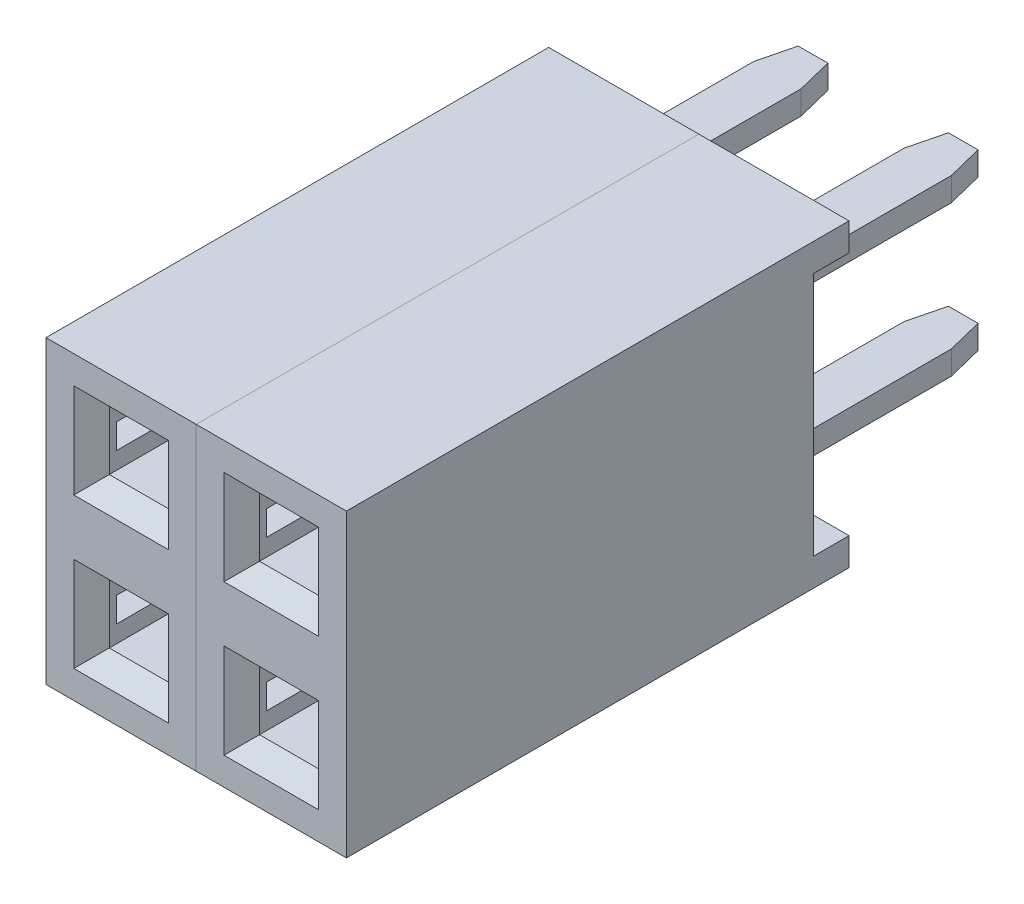
SolidWorks part; units mm, degrees
ref_plane "Спереди" through (0, 0, 0) normal (0, 0, 1) x (1, 0, 0)
ref_plane "Сверху" through (0, 0, 0) normal (0, 1, 0) x (1, 0, 0)
ref_plane "Справа" through (0, 0, 0) normal (1, 0, 0) x (0, 0, -1)
other "HX2.54D-Female"
sketch "Эскиз1" plane through (0, 0, 0) normal (0, 0, 1) x (1, 0, 0)
  line L0 (0, 1.27) -> (0, 0) construction
  line L1 (1.27, 2.54) -> (-1.27, 2.54)
  line L2 (1.27, 2.54) -> (1.27, 0)
  line L3 (1.27, 0) -> (-1.27, 0)
  line L4 (-1.27, 2.54) -> (-1.27, 0)
  line L5 (1.27, 2.54) -> (-1.27, 0) construction
  line L6 (1.27, 0) -> (-1.27, 2.54) construction
  dimension "D1" = 2.54
extrude "Бобышка-Вытянуть1" add sketch "Эскиз1" along normal blind 8.5
sketch "Эскиз2" plane through (0, 0, 0) normal (0, 0, -1) x (-1, 0, 0)
  line L0 (0, 1.27) -> (0, 0) construction
  line L1 (1, 1.48) -> (-1, 1.48)
  line L2 (1, 1.48) -> (1, 1.06)
  line L3 (1, 1.06) -> (-1, 1.06)
  line L4 (-1, 1.48) -> (-1, 1.06)
  line L5 (1, 1.48) -> (-1, 1.06) construction
  line L6 (1, 1.06) -> (-1, 1.48) construction
  line L7 (0, 1.27) -> (-1.27, 1.27) construction
  line L8 (-1.27, 0) -> (-1.27, 2.54) construction
  point P0 (0, 1.27)
  dimension "D1" = 2
  dimension "D2" = 0.42
extrude "Вырез-Вытянуть1" cut sketch "Эскиз2" against normal offset from surface (8.08 mm away) 0.42 up to face at (0, 1.27, 8.5)
sketch "Эскиз3" plane through (0, 0, 8.5) normal (0, 0, 1) x (1, 0, 0)
  line L0 (0, 1.27) -> (-1.27, 1.27) construction
  line L1 (-0.5, 0.77) -> (0.5, 0.77)
  line L2 (-0.5, 0.77) -> (-0.5, 1.77)
  line L3 (-0.5, 1.77) -> (0.5, 1.77)
  line L4 (0.5, 0.77) -> (0.5, 1.77)
  line L5 (-0.5, 0.77) -> (0.5, 1.77) construction
  line L6 (-0.5, 1.77) -> (0.5, 0.77) construction
  line L7 (-1.27, 2.54) -> (-1.27, 0) construction
  line L8 (0, 1.27) -> (0, 0) construction
  line L9 (-1.27, 0) -> (1.27, 0) construction
  point P0 (0, 1.27)
  dimension "D1" = 1
  dimension "D2" = 1
extrude "Вырез-Вытянуть2" cut sketch "Эскиз3" against normal offset from surface (6.5 mm away) 2 up to face at (0, 1.27, 0)
sketch "Эскиз4" plane through (-1.27, 0, 0) normal (-1, 0, 0) x (0, 0, 1)
  line L0 (0, 2.54) -> (0, 0) construction
  line L1 (0.6, 0.47) -> (0, 0.47)
  line L2 (0.6, 0.47) -> (0.6, 2.07)
  line L3 (0.6, 2.07) -> (0, 2.07)
  line L4 (0, 0.47) -> (0, 2.07)
  line L5 (0.6, 0.47) -> (0, 2.07) construction
  line L6 (0.6, 2.07) -> (0, 0.47) construction
  line L7 (0.3, 1.27) -> (0, 1.27) construction
  point P0 (0.3, 1.27)
  dimension "D1" = 0.6
  dimension "D2" = 1.6
extrude "Вырез-Вытянуть3" cut sketch "Эскиз4" against normal through all
ref_plane "Плоскость1" through (0, 1.27, 0) normal (0, -1, 0) x (-1, 0, 0)
sketch "Эскиз6" plane through (0, 1.27, 0) normal (0, -1, 0) x (-1, 0, 0)
  line L1 (-1, -8.08) -> (-1, -0.6) construction
  line L2 (1, -8.08) -> (1, -0.6) construction
  line L4 (-1.27, 0) -> (1.27, 0) construction
  line L10 (-1, -0.6) -> (1, -0.6) construction
  line L18 (-0.4, 0) -> (0.4, 0)
  line L19 (-0.6, -0.6) -> (-0.4, -0.6)
  line L20 (-1, -2.6) -> (-1, -0.85)
  line L21 (1, -2.6) -> (1, -0.85)
  line L22 (-0.4, -0.6) -> (-0.4, 0)
  line L23 (0.4, -0.6) -> (0.4, 0)
  line L24 (0, 0) -> (0, -0.6) construction
  line L25 (-1, -2.6) -> (-0.8133, -6.1)
  line L26 (-0.8133, -6.1) -> (-0.45, -6.75)
  line L27 (-0.45, -6.75) -> (-0.3, -6.35)
  line L28 (-0.3, -6.35) -> (-0.5, -2.6)
  line L29 (-0.5, -2.6) -> (-0.5, -1.7)
  line L30 (-0.5, -1.7) -> (0, -1.7) construction
  line L31 (0.5, -1.7) -> (0.5, -2.6)
  line L32 (0.5, -2.6) -> (0.3, -6.35)
  line L33 (0.3, -6.35) -> (0.45, -6.75)
  line L34 (0.45, -6.75) -> (0.8133, -6.1)
  line L35 (0.8133, -6.1) -> (1, -2.6)
  line L36 (-1, -2.6) -> (-0.5, -2.6) construction
  line L37 (0.5, -2.6) -> (-0.5, -2.6) construction
  line L38 (1, -2.6) -> (0.5, -2.6) construction
  line L39 (-0.3, -6.35) -> (0.3, -6.35) construction
  line L40 (-0.45, -6.75) -> (0.45, -6.75) construction
  line L41 (-0.8133, -6.1) -> (0.8133, -6.1) construction
  line L42 (0, -1.7) -> (0.5, -1.7) construction
  line L43 (0, -1.7) -> (0, -0.6) construction
  line L44 (-1, -0.85) -> (-0.6, -0.6)
  line L45 (1, -0.85) -> (0.6, -0.6)
  line L46 (-1, -0.85) -> (1, -0.85) construction
  line L47 (0.4, -0.6) -> (0.6, -0.6)
  arc A0 (-0.5, -1.7) -> (0.5, -1.7) centre (0, -1.7) cw
  dimension "D1" = 0.8
  dimension "D2" = 0.6
  dimension "D3" = 1
  dimension "D4" = 1.2
  dimension "D5" = 0.25
  dimension "D6" = 1.1
  dimension "D7" = 2
  dimension "D8" = 0.4
  dimension "D9" = 0.25
  dimension "D10" = 3.5
  dimension "D11" = 0.9
  dimension "D12" = 1.2
extrude "Бобышка-Вытянуть2" add sketch "Эскиз6" along normal mid plane 0.4 separate body contours L29 A0 L31 L32 L33 L34 L35 L21 L45 L19 L44 L20 L25 L26 L27 L28 | L19 L23 L18 L22
chamfer "Фаска1" distance 0.3 angle 45 4 edges at (0, 0.77, 8.5) (0.5, 1.27, 8.5) (0, 1.77, 8.5) (-0.5, 1.27, 8.5)
sketch "Sketch1" plane through (0, 0, 0) normal (0, 0, -1) x (-1, 0, 0)
  line L1 (-0.4, 1.47) -> (0.4, 1.47)
  line L2 (-0.4, 1.47) -> (-0.4, 1.07)
  line L3 (-0.4, 1.07) -> (0.4, 1.07)
  line L4 (0.4, 1.47) -> (0.4, 1.07)
extrude "Boss-Extrude1" add sketch "Sketch1" along normal blind 3.2
sketch "Sketch2" plane through (0, 1.47, 0) normal (0, 1, 0) x (1, 0, 0)
  line L0 (-0.4, 2.6) -> (0.4, 2.6) construction
  line L1 (-0.4, -0.6) -> (-0.4, 3.2) construction
  line L2 (0.4, -0.6) -> (0.4, 3.2) construction
  line L3 (-0.4, 3.2) -> (0.4, 3.2) construction
  line L4 (0, 3.2) -> (0, 2.6) construction
  line L5 (-0.25, 3.2) -> (-0.25, 2.6) construction
  line L6 (-0.25, 3.2) -> (-0.4, 2.6)
  line L7 (-0.4, 2.6) -> (-0.5333, 2.6)
  line L8 (-0.5333, 2.6) -> (-0.5333, 3.3233)
  line L9 (-0.5333, 3.3233) -> (-0.25, 3.3233)
  line L10 (-0.25, 3.3233) -> (-0.25, 3.2)
  line L11 (-0.25, 3.2) -> (-0.2501, 3.2095)
  line L12 (0.4, 2.6) -> (0.5333, 2.6)
  line L13 (0.25, 3.2) -> (0.4, 2.6)
  line L14 (0.25, 3.3233) -> (0.25, 3.2)
  line L15 (0.5333, 2.6) -> (0.5333, 3.3233)
  line L16 (0.5333, 3.3233) -> (0.25, 3.3233)
  dimension "D1" = 0.6
  dimension "D2" = 0.25
extrude "Cut-Extrude1" cut sketch "Sketch2" against normal blind 1
pattern_linear "LPattern1" count 2 spacing 2.54 along (0, -1, 0) of "Бобышка-Вытянуть1", "Вырез-Вытянуть1", "Вырез-Вытянуть2", "Вырез-Вытянуть3", "Бобышка-Вытянуть2", "Фаска1", "Boss-Extrude1", "Cut-Extrude1"
sketch "Sketch3" plane through (-1.27, 0, 0) normal (-1, 0, 0) x (0, 0, 1)
  line L0 (0.6, -2.07) -> (0.6, -0.47) construction
  line L1 (-0.1197, 0.5937) -> (0.6, 0.5937)
  line L2 (-0.1197, 0.5937) -> (-0.1197, -0.5784)
  line L3 (-0.1197, -0.5784) -> (0.6, -0.5784)
  line L4 (0.6, 0.5937) -> (0.6, -0.5784)
extrude "Cut-Extrude2" cut sketch "Sketch3" against normal blind 3
pattern_linear "LPattern2" count 2 spacing 2.54 along (1, 0, 0) of bodies 149
